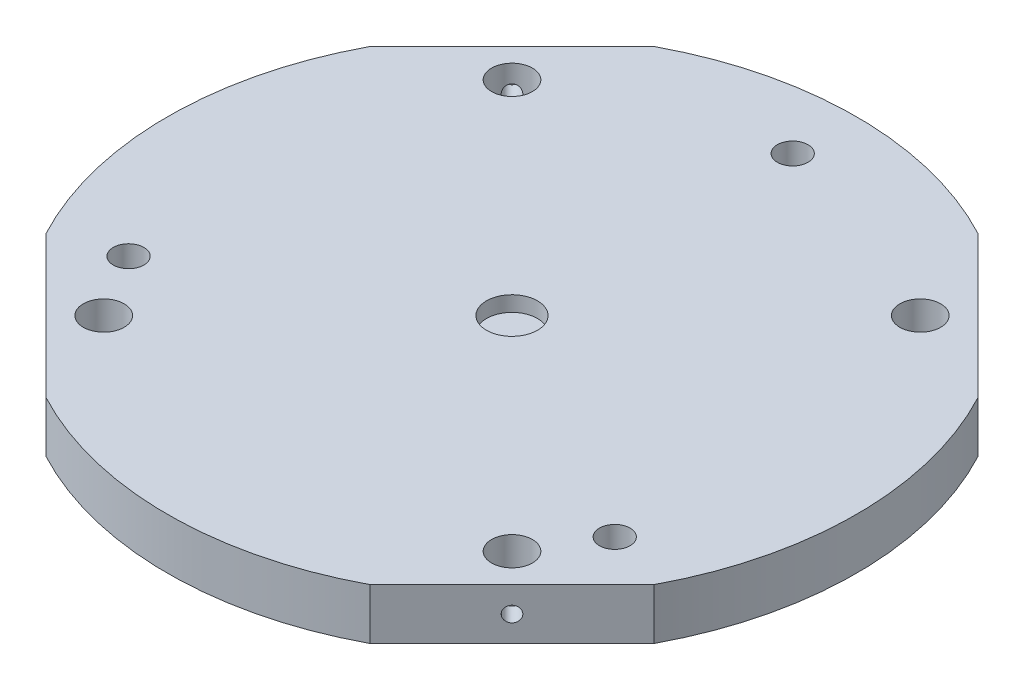
SolidWorks part; units mm, degrees
ref_plane "Front Plane" through (0, 0, 0) normal (0, 0, 1) x (1, 0, 0)
ref_plane "Top Plane" through (0, 0, 0) normal (0, 1, 0) x (1, 0, 0)
ref_plane "Right Plane" through (0, 0, 0) normal (1, 0, 0) x (0, 0, -1)
sketch "Sketch1" plane through (0, 0, 0) normal (0, 1, 0) x (1, 0, 0)
  circle A0 centre (0, 0) radius 67.5
  dimension "D1" = 135
extrude "Boss-Extrude1" add sketch "Sketch1" along normal blind 10
hole_wizard "Ø6.0mm Dowel Hole1" positions "Sketch2" profile "Sketch3" hole size "Ø6.0" standard "ANSI Metric" end condition through all
sketch "Sketch2" plane through (0, 10, 0) normal (0, 1, 0) x (1, 0, 0)
  line L0 (0, 0) -> (0, 55) construction
  line L2 (0, 0) -> (47.6314, -27.5) construction
  point P0 (0, 55)
  point P14 (47.6314, -27.5)
  point P15 (-47.6314, -27.5)
  dimension "D1" = 55
  dimension "D3" = 55
  dimension "D4" = 120
  dimension "D2" = 3
sketch "Sketch3" plane through (0, 10, -55) normal (1, 0, 0) x (0, 0, 1)
  line L0 (0, 0) -> (0, 10)
  line L1 (0, 10) -> (3, 10)
  line L2 (3, 10) -> (3, 0)
  line L5 (3, 0) -> (0, 0)
  line L11 (0, -6.35) -> (0, 107.95) construction
  dimension "Thru Hole Dia." = 6
  dimension "Thru Hole Depth" = 10
sketch "Sketch4" plane through (0, 10, 0) normal (0, 1, 0) x (1, 0, 0)
  line L0 (0, 67.5) -> (0, -67.5) construction
  line L1 (-67.5, 0) -> (67.5, 0) construction
  circle A0 centre (0, 0) radius 67.5 construction
  circle A1 centre (-40, 40) radius 4
  circle A2 centre (40, 40) radius 4
  circle A3 centre (40, -40) radius 4
  circle A4 centre (-40, -40) radius 4
  point P7 (0, 0)
  point P12 (0, 0)
  dimension "D3" = 8
  dimension "D1" = 40
  dimension "D2" = 40
extrude "Cut-Extrude1" cut sketch "Sketch4" against normal through all and the other way through all
sketch "Sketch5" plane through (0, 10, 0) normal (0, 1, 0) x (1, 0, 0)
  line L0 (-44.5962, 41.0607) -> (-41.0607, 44.5962) construction
  line L1 (-42.8284, 42.8284) -> (0, 0) construction
  line L2 (0, 67.5) -> (0, -67.5) construction
  line L3 (-31.7437, 59.57) -> (-59.57, 31.7437)
  line L4 (59.57, 31.7437) -> (31.7437, 59.57)
  line L5 (31.7437, -59.57) -> (59.57, -31.7437)
  line L6 (-59.57, -31.7437) -> (-31.7437, -59.57)
  line L7 (0, 0) -> (-45.6569, -45.6569) construction
  circle A0 centre (0, 0) radius 67.5 construction
  circle A1 centre (-40, 40) radius 4 construction
  point P5 (-42.8284, 42.8284)
  point P14 (0, 0)
  point P15 (-45.6569, 45.6569)
  dimension "D1" = 5
  dimension "D2" = 45
  dimension "D3" = 4
  dimension "D4" = 4
extrude "Cut-Extrude-Thin1" cut sketch "Sketch5" against normal through all thin
hole_wizard "Ø3.0mm Dowel Hole1" positions "Sketch6" profile "Sketch7" hole size "Ø3.0" standard "ANSI Metric"
sketch "Sketch6" plane through (45.6569, 0, 45.6569) normal (0.7071, 0, 0.7071) x (0.7071, 0, -0.7071)
  line L0 (0, 0) -> (0, 10) construction
  line L1 (-19.6762, 0) -> (19.6762, 0) construction
  line L2 (-19.6762, 10) -> (19.6762, 10) construction
  point P0 (0, 5)
sketch "Sketch7" plane through (45.6569, 5, 45.6569) normal (0, 1, 0) x (0.7071, 0, -0.7071)
  line L0 (0, 0) -> (0, 4)
  line L1 (0, 4) -> (1.5, 4)
  line L2 (1.5, 4) -> (1.5, 0)
  line L5 (1.5, 0) -> (0, 0)
  line L11 (0, -6.35) -> (0, 107.95) construction
  dimension "Thru Hole Dia." = 3
  dimension "Thru Hole Depth" = 4
pattern_circular "CirPattern1" count 4 over 360 about axis through (0, 10, 0) along (0, -1, 0) of "Ø3.0mm Dowel Hole1"
sketch "Sketch8" plane through (0, 10, 0) normal (0, 1, 0) x (1, 0, 0)
  circle A0 centre (0, 0) radius 5
  dimension "D1" = 10
extrude "Cut-Extrude2" cut sketch "Sketch8" against normal blind 3 and the other way through all
equation "\"Plate Thickness\"= 10mm"
equation "\"Plate Diameter\"= 135mm"
equation "\"D1@Sketch1\"=\"Plate Diameter\""
equation "\"D1@Boss-Extrude1\"=\"Plate Thickness\""
